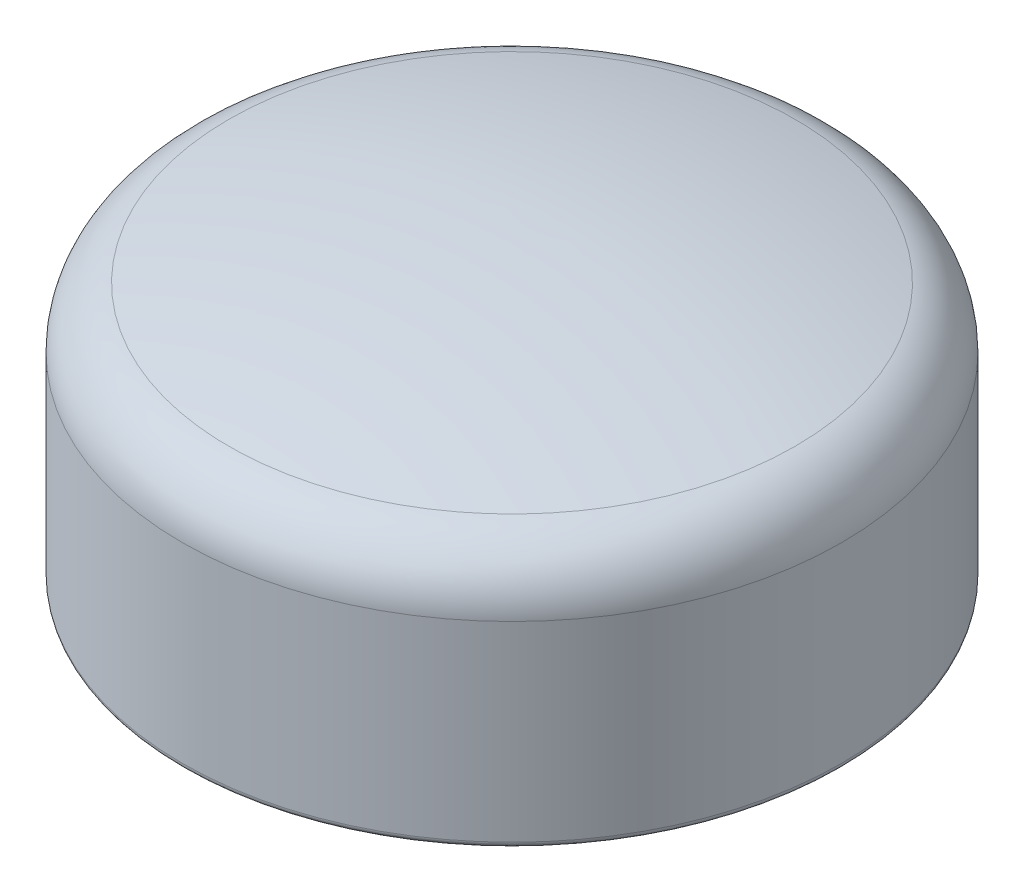
SolidWorks part; units mm, degrees
material "Nylon 101"
ref_plane "Front Plane" through (0, 0, 0) normal (0, 0, 1) x (1, 0, 0)
ref_plane "Top Plane" through (0, 0, 0) normal (0, 1, 0) x (1, 0, 0)
ref_plane "Right Plane" through (0, 0, 0) normal (1, 0, 0) x (0, 0, -1)
sketch "Sketch1" plane through (0, 0, 0) normal (0, 0, 1) x (1, 0, 0)
  line L0 (0, -281.8326) -> (0, 13809.795) construction
  line L1 (13.5, 8.081) -> (13.5, 0)
  line L2 (13.5, 0) -> (12.5, 0)
  line L3 (12.5, 0) -> (12.5, 8.081)
  line L4 (0, 12.081) -> (0, 11.081)
  line L5 (13.5, 10) -> (13.5, 8.081) construction
  line L6 (11.344, 9.5875) -> (11.6028, 10.5534) construction
  line L7 (11.344, 9.5875) -> (2.2489, 12.0245) construction
  arc A1 (11.344, 9.5875) -> (0, 11.081) centre (0, -32.7488) ccw
  arc A2 (12.5, 8.081) -> (11.344, 9.5875) centre (10.9403, 8.081) ccw
  arc A3 (11.6028, 10.5534) -> (0, 12.081) centre (0, -32.7488) ccw
  arc A4 (13.5, 8.081) -> (11.6028, 10.5534) centre (10.9403, 8.081) ccw
  arc A5 (13.5, 10) -> (11.6028, 10.5534) centre (0, -32.7488) ccw construction
  dimension "D1" = 25
  dimension "D6" = 15
  dimension "D2" = 1
  dimension "D3" = 10
  dimension "D4" = 3
  dimension "D5" = 1
revolve "Revolve1" add sketch "Sketch1" angle 360 about L0
fillet "Fillet1" radius 0.25 2 edges at (12.5, 0, 0) (13.5, 0, 0)
